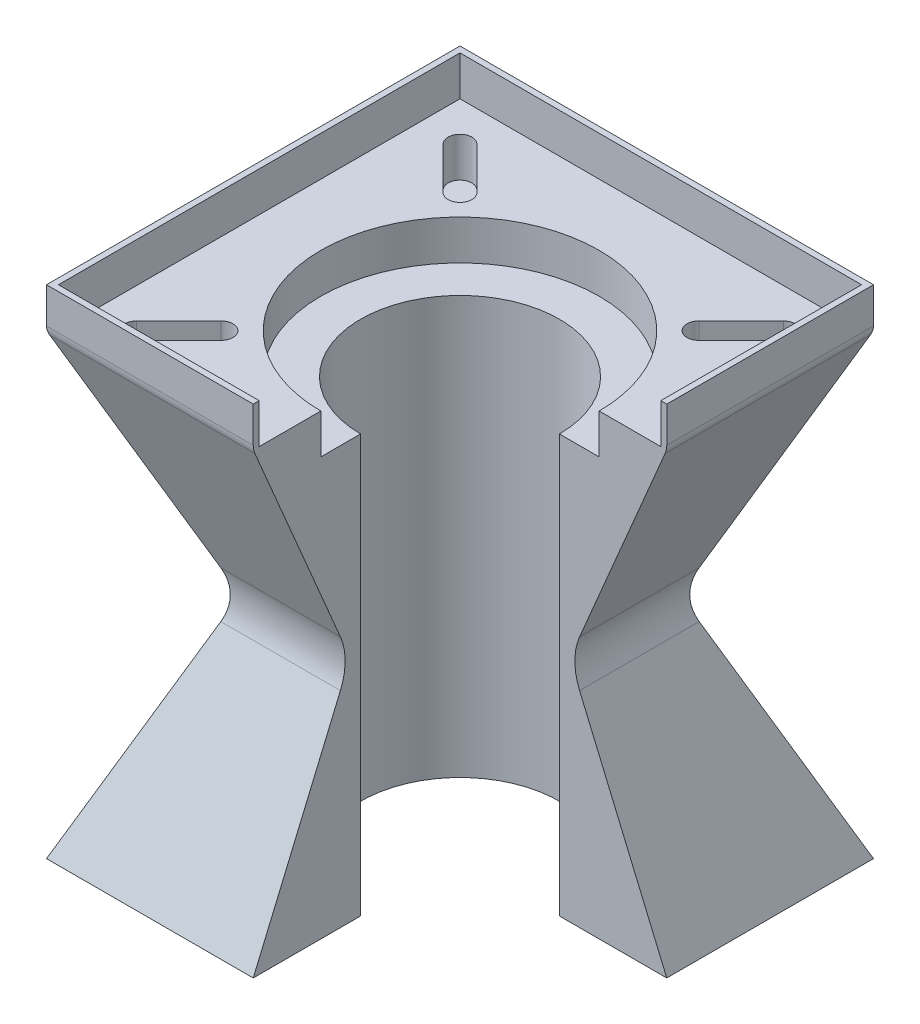
SolidWorks part; units mm, degrees
material "Cast Stainless Steel"
ref_plane "Front Plane" through (0, 0, 0) normal (0, 0, 1) x (1, 0, 0)
ref_plane "Top Plane" through (0, 0, 0) normal (0, 1, 0) x (1, 0, 0)
ref_plane "Right Plane" through (0, 0, 0) normal (1, 0, 0) x (0, 0, -1)
sketch "Sketch1" plane through (0, 0, 0) normal (0, 1, 0) x (1, 0, 0)
  line L1 (-52, 52) -> (52, 52)
  line L2 (-52, 52) -> (-52, -52)
  line L3 (-52, -52) -> (52, -52)
  line L4 (52, 52) -> (52, -52)
  line L5 (-52, 52) -> (52, -52) construction
  line L6 (-52, -52) -> (52, 52) construction
  point P0 (0, 0)
  dimension "D1" = 104
  dimension "D2" = 104
extrude "Boss-Extrude1" add sketch "Sketch1" along normal blind 125
sketch "Sketch2" plane through (0, 0, 52) normal (0, 0, 1) x (1, 0, 0)
  line L0 (52, 125) -> (52, 115)
  line L1 (52, 125) -> (52, 0) construction
  line L2 (52, 115) -> (27.5927, 57.5)
  line L3 (27.5927, 57.5) -> (52, 0)
  line L4 (-52, 125) -> (-52, 115)
  line L5 (-52, 125) -> (-52, 0) construction
  line L6 (-52, 115) -> (-27.5927, 57.5)
  line L7 (-27.5927, 57.5) -> (-52, 0)
  line L8 (52, 115) -> (52, 0)
  line L9 (-52, 115) -> (-52, 0)
  line M7 (52, 0) -> (52, 125)
  line M9 (-52, 125) -> (-52, 0)
  dimension "D1" = 10
  dimension "D2" = 57.5
  dimension "D3" = 23
  dimension "D4" = 23
  dimension "D5" = 23
  dimension "D6" = 57.5
  dimension "D7" = 57.5
  dimension "D8" = 23
  dimension "D9" = 115
  dimension "D10" = 115
extrude "Cut-Extrude3" cut sketch "Sketch2" against normal blind 125 contours L7 L6 M9 | L2 L3 M7
sketch "Sketch3" plane through (0, 0, 0) normal (1, 0, 0) x (0, 0, -1)
  line L0 (-52, 115) -> (-27.5927, 57.5)
  line L1 (52, 57.5) -> (-52, 57.5) construction
  line L2 (-27.5927, 57.5) -> (-52, 0)
  line L3 (-52, 0) -> (-52, 115)
  line L4 (52, 115) -> (27.5927, 57.5)
  line L5 (27.5927, 57.5) -> (52, 0)
  line L6 (52, 0) -> (52, 115)
  dimension "D1" = 115
  dimension "D2" = 23
  dimension "D3" = 23
  dimension "D4" = 23
  dimension "D5" = 23
extrude "Cut-Extrude4" cut sketch "Sketch3" against normal through all both and the other way through all
sketch "Sketch4" plane through (0, 125, 0) normal (0, 1, 0) x (1, 0, 0)
  circle A0 centre (0, 0) radius 25
extrude "Cut-Extrude5" cut sketch "Sketch4" against normal through all both
sketch "Sketch5" plane through (0, 125, 0) normal (0, 1, 0) x (1, 0, 0)
  line L1 (-50.5, -50.5) -> (50.5, -50.5)
  line L2 (-50.5, -50.5) -> (-50.5, 50.5)
  line L3 (-50.5, 50.5) -> (50.5, 50.5)
  line L4 (50.5, -50.5) -> (50.5, 50.5)
  line L5 (-50.5, -50.5) -> (50.5, 50.5) construction
  line L6 (-50.5, 50.5) -> (50.5, -50.5) construction
  point P0 (0, 0)
extrude "Cut-Extrude6" cut sketch "Sketch5" against normal blind 10
sketch "Sketch6" plane through (0, 115, 0) normal (0, 1, 0) x (1, 0, 0)
  line L0 (0, 0) -> (52, 0)
  line L1 (52, -52) -> (52, 52) construction
  line L2 (52, 0) -> (52, -52)
  line L4 (0, -52) -> (0, 0)
  line L5 (-52, -52) -> (52, -52) construction
  line L6 (0, -52) -> (52, -52)
extrude "Cut-Extrude7" cut sketch "Sketch6" against normal blind 125
sketch "Sketch7" plane through (0, 125, 0) normal (0, 1, 0) x (1, 0, 0)
  line L0 (0, 0) -> (52, 0)
  line L1 (52, -52) -> (52, 52) construction
  line L2 (52, 0) -> (52, -52)
  line L3 (52, -52) -> (0, -52)
  line L4 (0, -52) -> (0, 0)
extrude "Cut-Extrude8" cut sketch "Sketch7" against normal blind 125
sketch "Sketch8" plane through (0, 115, 0) normal (0, 1, 0) x (1, 0, 0)
  circle A0 centre (0, 0) radius 35
extrude "Cut-Extrude9" cut sketch "Sketch8" against normal blind 10
sketch "Sketch9" plane through (0, 115, 0) normal (0, 1, 0) x (1, 0, 0)
  line L0 (0, 58.2081) -> (0, -58.2081) construction
  line L1 (-66.5624, 0) -> (66.5624, 0) construction
  line L2 (-52, 52) -> (54.066, -54.066) construction
  line L3 (52, 52) -> (-52, -52) construction
  line L4 (-40.6586, 40.6586) -> (-30.052, 30.052) construction
  line L5 (-38.5373, 42.78) -> (-27.9307, 32.1734)
  line L6 (-42.78, 38.5373) -> (-32.1734, 27.9307)
  line L7 (40.6586, 40.6586) -> (30.052, 30.052) construction
  line L8 (38.5373, 42.78) -> (27.9307, 32.1734)
  line L9 (42.78, 38.5373) -> (32.1734, 27.9307)
  line L10 (-40.6586, -40.6586) -> (-30.052, -30.052) construction
  line L11 (-38.5373, -42.78) -> (-27.9307, -32.1734)
  line L12 (-42.78, -38.5373) -> (-32.1734, -27.9307)
  arc A0 (-38.5373, 42.78) -> (-42.78, 38.5373) centre (-40.6586, 40.6586) ccw
  arc A1 (-32.1734, 27.9307) -> (-27.9307, 32.1734) centre (-30.052, 30.052) ccw
  arc A2 (38.5373, 42.78) -> (42.78, 38.5373) centre (40.6586, 40.6586) cw
  arc A3 (32.1734, 27.9307) -> (27.9307, 32.1734) centre (30.052, 30.052) cw
  arc A4 (-38.5373, -42.78) -> (-42.78, -38.5373) centre (-40.6586, -40.6586) cw
  arc A5 (-32.1734, -27.9307) -> (-27.9307, -32.1734) centre (-30.052, -30.052) cw
  point P4 (0, 0)
  point P8 (0, 0)
  point P15 (-35.3553, 35.3553)
  point P23 (35.3553, 35.3553)
  point P30 (-35.3553, -35.3553)
  dimension "D1" = 150
  dimension "D3" = 15
  dimension "D4" = 50
extrude "Cut-Extrude10" cut sketch "Sketch9" against normal blind 10
fillet "Fillet3" radius 5 4 edges at (-26, 115, 52) (-52, 115, 0) (52, 115, -26) (0, 115, -52)
fillet "Fillet4" radius 15 4 edges at (27.5927, 57.5, -13.7963) (-27.5927, 57.5, 0) (0, 57.5, -27.5927) (-13.7963, 57.5, 27.5927)
